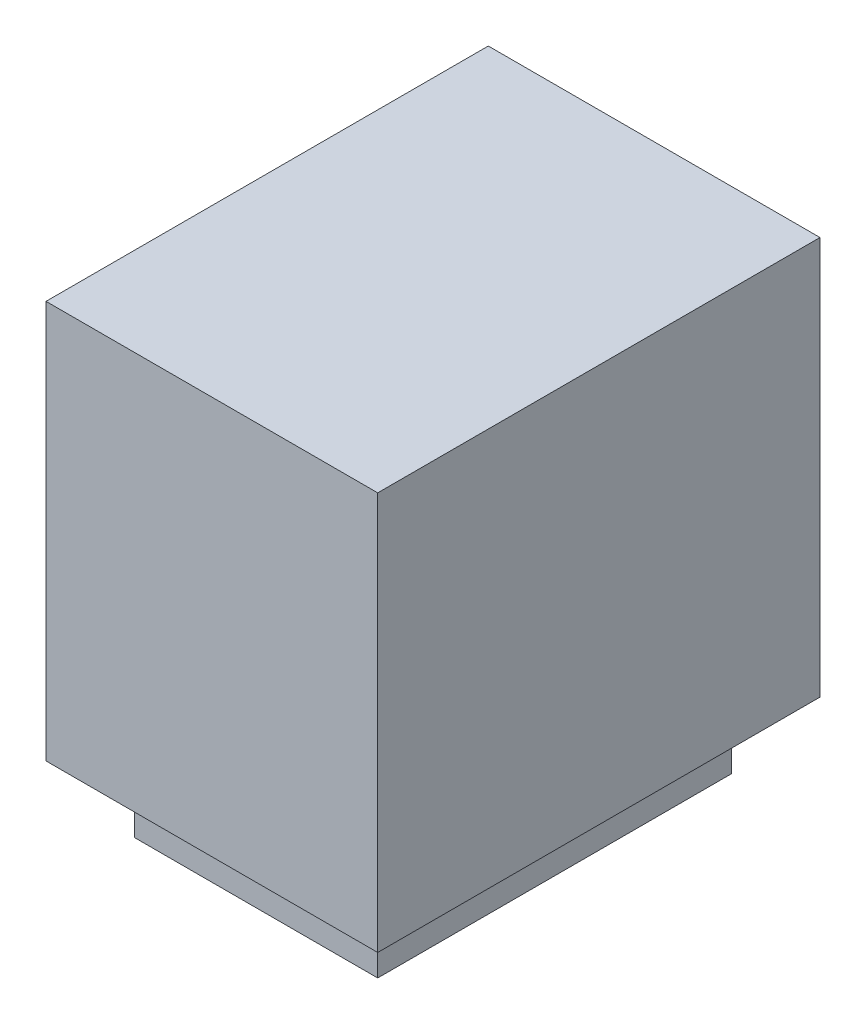
SolidWorks part; units mm, degrees
material "AISI 1020 Steel, Cold Rolled"
ref_plane "Front Plane" through (0, 0, 0) normal (0, 0, 1) x (1, 0, 0)
ref_plane "Top Plane" through (0, 0, 0) normal (0, 1, 0) x (1, 0, 0)
ref_plane "Right Plane" through (0, 0, 0) normal (1, 0, 0) x (0, 0, -1)
sketch "Sketch2" plane through (0, 0, 0) normal (0, 1, 0) x (1, 0, 0)
  line L0 (-9559.3915, 0) -> (468410.1826, 0) construction
  line L1 (0, -9559.3915) -> (0, 468410.1826) construction
  line L3 (-750, 1000) -> (750, 1000)
  line L4 (-750, 1000) -> (-750, -1000)
  line L5 (-750, -1000) -> (750, -1000)
  line L6 (750, 1000) -> (750, -1000)
  line L7 (0, -1000) -> (0, 1000) construction
  line L8 (-750, 0) -> (750, 0) construction
  point P4 (0, 0)
  dimension "D1" = 1500
  dimension "D2" = 2000
extrude "Boss-Extrude1" add sketch "Sketch2" along normal blind 1800
sketch "Sketch3" plane through (0, 0, 0) normal (0, 1, 0) x (1, 0, 0)
  line L1 (-550, 800) -> (550, 800)
  line L2 (-550, 800) -> (-550, -800)
  line L3 (-550, -800) -> (550, -800)
  line L4 (550, 800) -> (550, -800)
  line L5 (0, -800) -> (0, 800) construction
  line L6 (-550, 0) -> (550, 0) construction
  point P0 (0, 0)
  dimension "D1" = 1100
  dimension "1600" = 1600
extrude "Boss-Extrude2" add sketch "Sketch3" against normal blind 300
sketch "Sketch4" plane through (0, 0, 0) normal (0, 0, 1) x (1, 0, 0)
  line L1 (-454.4627, 1500) -> (445.5373, 1500)
  line L2 (-454.4627, 1500) -> (-454.4627, 300)
  line L3 (-454.4627, 300) -> (445.5373, 300)
  line L4 (445.5373, 1500) -> (445.5373, 300)
  line L5 (-4.4627, 300) -> (-4.4627, 1500) construction
  line L6 (-454.4627, 900) -> (445.5373, 900) construction
  point P0 (-4.4627, 900)
  dimension "D1" = 1200
  dimension "D2" = 900
extrude "Cut-Extrude1" cut sketch "Sketch4" along normal blind 50
sketch "Sketch5" plane through (0, 0, 0) normal (0, 0, 1) x (1, 0, 0)
  line L1 (-228.5962, 1118.7608) -> (371.4038, 1118.7608)
  line L2 (-228.5962, 1118.7608) -> (-228.5962, 718.7608)
  line L3 (-228.5962, 718.7608) -> (371.4038, 718.7608)
  line L4 (371.4038, 1118.7608) -> (371.4038, 718.7608)
  line L5 (71.4038, 718.7608) -> (71.4038, 1118.7608) construction
  line L6 (-228.5962, 918.7608) -> (371.4038, 918.7608) construction
  point P0 (71.4038, 918.7608)
  point P4 (-22.3137, 718.7608)
  point P5 (0, 0)
  dimension "D1" = 400
  dimension "D2" = 600
extrude "Boss-Extrude3" add sketch "Sketch5" against normal blind 50
sketch "Sketch6" plane through (0, 1800, 0) normal (0, 1, 0) x (1, 0, 0)
  line L1 (-150, 200) -> (150, 200)
  line L2 (-150, 200) -> (-150, -200)
  line L3 (-150, -200) -> (150, -200)
  line L4 (150, 200) -> (150, -200)
  line L5 (0, -200) -> (0, 200) construction
  line L6 (-150, 0) -> (150, 0) construction
  circle A0 centre (-1309.0703, 63.7534) radius 181.9177
  point P3 (0, 0)
  dimension "D1" = 400
  dimension "D2" = 300
